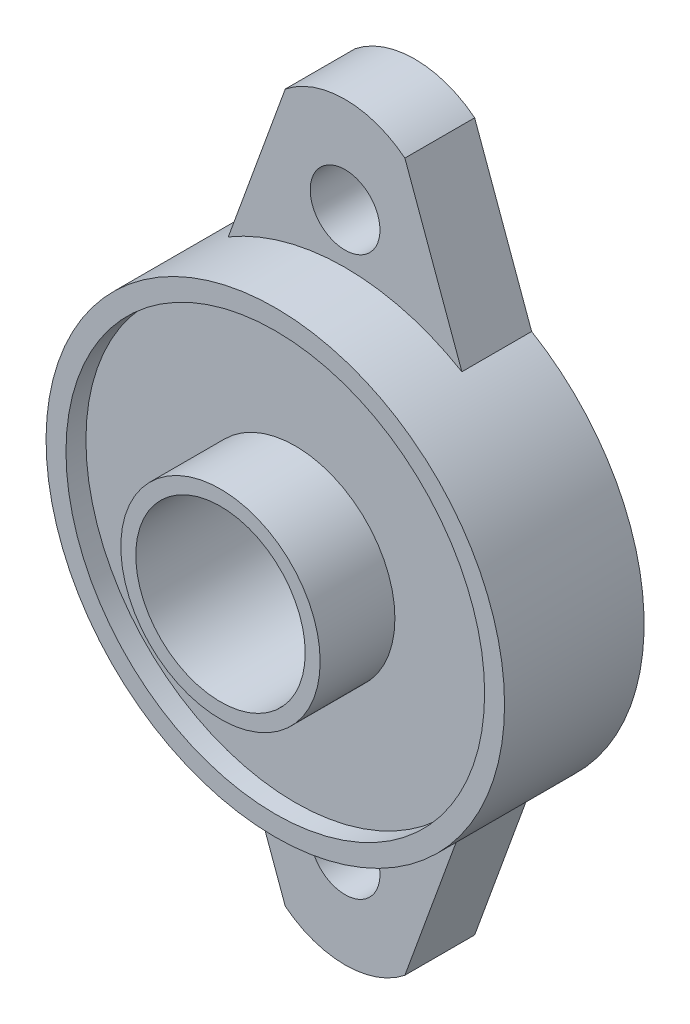
SolidWorks part; units mm, degrees
ref_plane "Plan de face" through (0, 0, 0) normal (0, 0, 1) x (1, 0, 0)
ref_plane "Plan de dessus" through (0, 0, 0) normal (0, 1, 0) x (1, 0, 0)
ref_plane "Plan de droite" through (0, 0, 0) normal (1, 0, 0) x (0, 0, -1)
sketch "Esquisse1" plane through (0, 0, 0) normal (0, 0, 1) x (1, 0, 0)
  line L0 (0, 0) -> (0, 28) construction
  line L1 (0, 0) -> (9.1812, 0) construction
  line L2 (9.1812, 0) -> (23, 0) construction
  line L3 (11.7174, 19.7914) -> (6, 35.5)
  line L4 (0, 28) -> (0, 37.6047) construction
  line L5 (11.7174, -19.7914) -> (6, -35.5)
  line L6 (-11.7174, -19.7914) -> (-6, -35.5)
  line L7 (-11.7174, 19.7914) -> (-6, 35.5)
  circle A0 centre (0, 28) radius 3.5
  circle A1 centre (0, 0) radius 8.5
  circle A2 centre (0, -28) radius 3.5
  arc A3 (11.7174, 19.7914) -> (11.7174, -19.7914) centre (0, 0) cw
  arc A4 (6, 35.5) -> (-6, 35.5) centre (0, 28) ccw
  arc A5 (6, -35.5) -> (-6, -35.5) centre (0, -28) cw
  arc A6 (-11.7174, 19.7914) -> (-11.7174, -19.7914) centre (0, 0) ccw
  dimension "D1" = 7
  dimension "D2" = 56
  dimension "D3" = 17
  dimension "D4" = 23
  dimension "D5" = 35.5
  dimension "D6" = 20
  dimension "D7" = 6
extrude "Boss.-Extru.1" add sketch "Esquisse1" along normal blind 7
sketch "Esquisse2" plane through (0, 0, 7) normal (0, 0, 1) x (1, 0, 0)
  circle A0 centre (0, 0) radius 8.5
  circle A1 centre (0, 0) radius 23
  circle A2 centre (0, 0) radius 8.5 construction
  arc A3 (11.7174, -19.7914) -> (11.7174, 19.7914) centre (0, 0) ccw construction
extrude "Boss.-Extru.2" add sketch "Esquisse2" along normal blind 7
sketch "Esquisse3" plane through (0, 0, 14) normal (0, 0, 1) x (1, 0, 0)
  circle A0 centre (0, 0) radius 8.5
  circle A1 centre (0, 0) radius 10
  circle A2 centre (0, 0) radius 8.5 construction
  dimension "D1" = 1.5
extrude "Boss.-Extru.3" add sketch "Esquisse3" along normal blind 5.5
sketch "Esquisse4" plane through (0, 0, 14) normal (0, 0, 1) x (1, 0, 0)
  circle A0 centre (0, 0) radius 10
  circle A1 centre (0, 0) radius 21
  circle A2 centre (0, 0) radius 23 construction
  circle A3 centre (0, 0) radius 10 construction
  dimension "D1" = 2
extrude "Enlèv. mat.-Extru.1" cut sketch "Esquisse4" against normal blind 2
